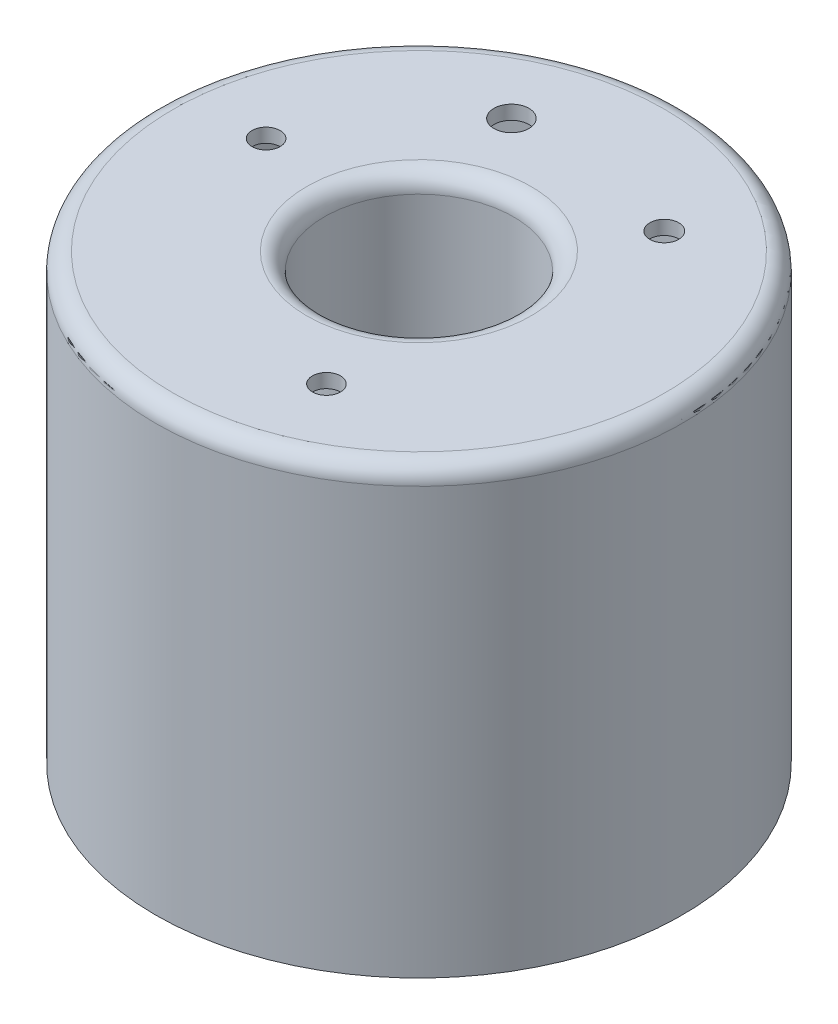
SolidWorks part; units mm, degrees
ref_plane "Front Plane" through (0, 0, 0) normal (0, 0, 1) x (1, 0, 0)
ref_plane "Top Plane" through (0, 0, 0) normal (0, 1, 0) x (1, 0, 0)
ref_plane "Right Plane" through (0, 0, 0) normal (1, 0, 0) x (0, 0, -1)
sketch "Sketch1" plane through (0, 0, 0) normal (0, 1, 0) x (1, 0, 0)
  circle A1 centre (0, 0) radius 38.1635
  circle A2 centre (0, 0) radius 13.716
  dimension "D2" = 76.327
  dimension "D3" = 27.432
extrude "Boss-Extrude3" add sketch "Sketch1" along normal blind 64.262
sketch "Sketch3" plane through (0, 0, 0) normal (0, -1, 0) x (-1, 0, 0)
  circle A0 centre (0, 0) radius 38.1
  circle A1 centre (0, 0) radius 14.097
  dimension "D1" = 76.2
  dimension "D2" = 28.194
extrude "Cut-Extrude1" cut sketch "Sketch3" against normal blind 62.23
fillet "Fillet1" radius 2.54 2 edges at (0, 64.262, 13.716) (0, 64.262, 38.1635)
sketch "Sketch5" plane through (0, 64.262, 0) normal (0, 1, 0) x (1, 0, 0)
  line L0 (0, 0) -> (-25.2152, 3.0586) construction
  line L1 (0, 0) -> (9.9587, -23.3663) construction
  line L2 (0, 0) -> (15.2564, 20.3077) construction
  line L3 (-25.2152, 3.0586) -> (-9.9587, 23.3663) construction
  line L4 (-9.9587, 23.3663) -> (15.2564, 20.3077) construction
  circle A0 centre (15.2564, 20.3077) radius 2.0937
  circle A1 centre (-25.2152, 3.0586) radius 2.032
  circle A2 centre (9.9587, -23.3663) radius 2.032
  circle A3 centre (-9.9587, 23.3663) radius 2.54
  dimension "D3" = 25.4
  dimension "D5" = 5.08
  dimension "D6" = 4.064
  dimension "D1" = 120
  dimension "D2" = 120
  dimension "D4" = 25.4
extrude "Cut-Extrude2" cut sketch "Sketch5" against normal blind 2.54
